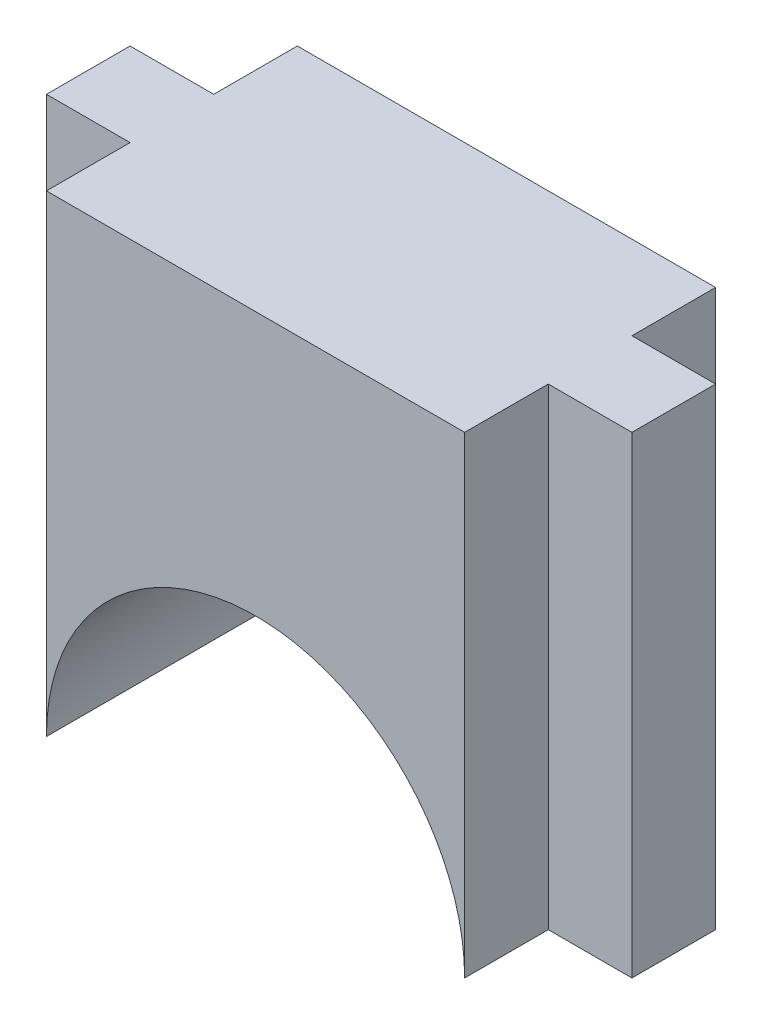
SolidWorks part; units mm, degrees
ref_plane "前视基准面" through (0, 0, 0) normal (0, 0, 1) x (1, 0, 0)
ref_plane "上视基准面" through (0, 0, 0) normal (0, 1, 0) x (1, 0, 0)
ref_plane "右视基准面" through (0, 0, 0) normal (1, 0, 0) x (0, 0, -1)
sketch "Sketch1" plane through (0, 0, 0) normal (0, 0, 1) x (1, 0, 0)
  line L0 (7.5, 0) -> (7.5, 16.95)
  line L1 (-7.5, 16.95) -> (-7.5, 0)
  line L2 (-7.5, 16.95) -> (7.5, 16.95)
  arc A0 (7.5, 0) -> (-7.5, 0) centre (0, 0) ccw
  point P5 (0, 0)
  point P7 (7.5, 0)
  point P8 (7.5, 0)
  point P9 (7.5, 16.95)
  point P10 (-7.5, 16.95)
  point P11 (0, 0)
  point P12 (-7.5, 0)
  point P13 (-7.5, 0)
  dimension "D2" = 7.5
  dimension "D1" = 15
  dimension "D3" = 16.95
extrude "Extrude1" add sketch "Sketch1" along normal blind 9
sketch "Sketch2" plane through (7.5, 0, 0) normal (1, 0, 0) x (0, 0, -1)
  line L0 (-9, 16.95) -> (0, 16.95) construction
  line L1 (-6, 16.95) -> (-3, 16.95)
  line L2 (-6, 16.95) -> (-6, 0)
  line L3 (-6, 0) -> (-3, 0)
  line L4 (-3, 16.95) -> (-3, 0)
  line L5 (-9, 0) -> (0, 0) construction
  line L6 (0, 0) -> (0, 16.95) construction
  dimension "D1" = 3
  dimension "D2" = 3
extrude "Extrude2" add sketch "Sketch2" along normal blind 3
ref_plane "Plane1" through (0, 0, 0) normal (-1, 0, 0) x (0, 0, 1)
mirror "Mirror1" about plane through (0, 0, 0) normal (-1, 0, 0) of "Extrude2"
